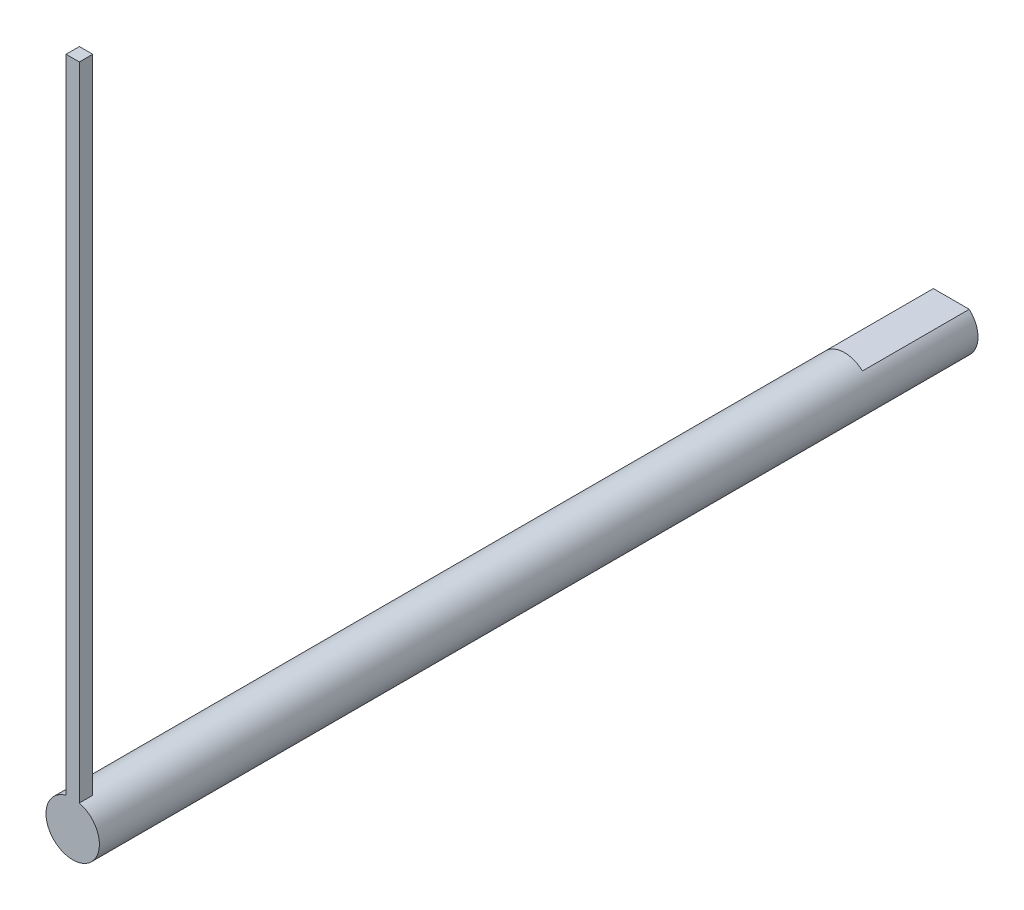
SolidWorks part; units mm, degrees
ref_plane "Front Plane" through (0, 0, 0) normal (0, 0, 1) x (1, 0, 0)
ref_plane "Top Plane" through (0, 0, 0) normal (0, 1, 0) x (1, 0, 0)
ref_plane "Right Plane" through (0, 0, 0) normal (1, 0, 0) x (0, 0, -1)
sketch "Sketch1" plane through (0, 0, 0) normal (0, 0, 1) x (1, 0, 0)
  circle A0 centre (0, 0) radius 2
  dimension "D1" = 4
extrude "Boss-Extrude1" add sketch "Sketch1" along normal blind 65.8
sketch "Sketch2" plane through (0, 0, 0) normal (0, 0, -1) x (-1, 0, 0)
  line L0 (-1.3452, 1.48) -> (1.3452, 1.48)
  line L1 (0, -2) -> (4.5119, -2) construction
  arc A0 (1.3452, 1.48) -> (-1.3452, 1.48) centre (0, 0) ccw
  circle A1 centre (0, 0) radius 2 construction
  dimension "D1" = 3.48
extrude "Cut-Extrude1" cut sketch "Sketch2" against normal blind 8
sketch "Sketch3" plane through (0, 0, 65.8) normal (0, 0, 1) x (1, 0, 0)
  line L0 (-0.5, 0) -> (-0.5, 50)
  line L1 (-0.5, 0) -> (0.5, 0)
  line L2 (0, 0) -> (0, 50) construction
  line L3 (-0.5, 50) -> (0.5, 50)
  line L4 (0.5, 0) -> (0.5, 50)
  dimension "D1" = 0.5
  dimension "D2" = 50
extrude "Boss-Extrude2" add sketch "Sketch3" against normal blind 1
